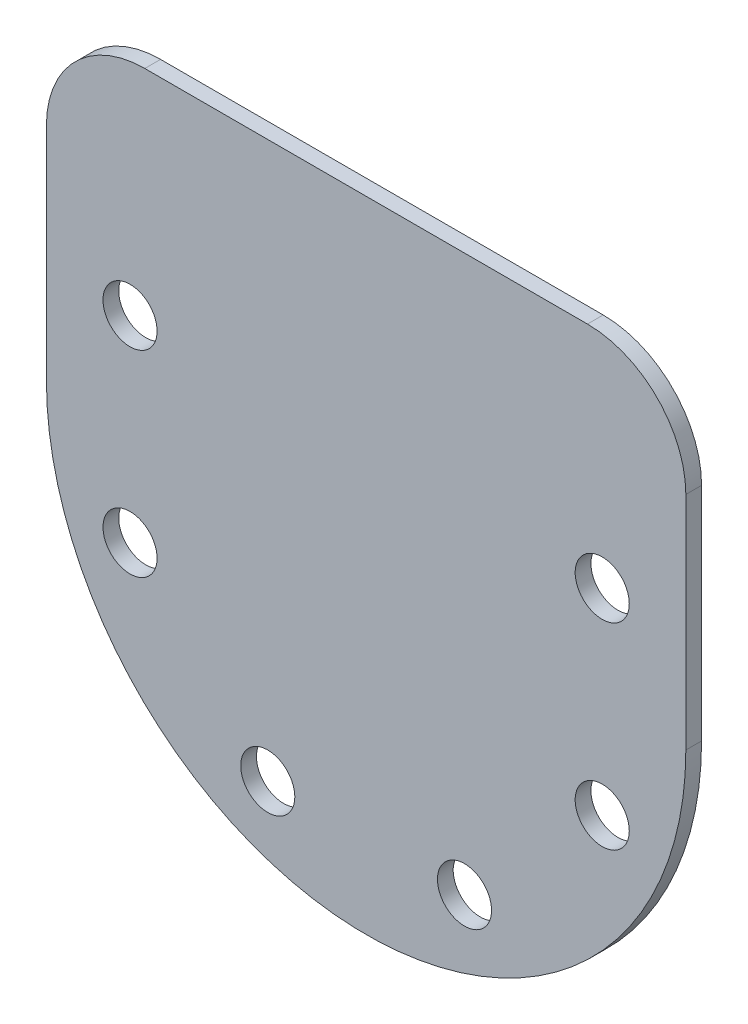
SolidWorks part; units mm, degrees
ref_plane "Front" through (0, 0, 0) normal (0, 0, 1) x (1, 0, 0)
ref_plane "Top" through (0, 0, 0) normal (0, 1, 0) x (1, 0, 0)
ref_plane "Right" through (0, 0, 0) normal (1, 0, 0) x (0, 0, -1)
sketch "Sketch1" plane through (0, 0, 0) normal (0, 0, 1) x (1, 0, 0)
  line L2 (-32.5, 0) -> (-32.5, 32.5)
  line L3 (-32.5, 32.5) -> (32.5, 32.5)
  line L4 (32.5, 0) -> (32.5, 32.5)
  line L5 (-22.981, -22.981) -> (32.5, 32.5) construction
  line L6 (-32.5, 32.5) -> (22.981, -22.981) construction
  arc A0 (-32.5, 0) -> (32.5, 0) centre (0, 0) ccw
  dimension "D1" = 65
  dimension "D2" = 65
extrude "Boss-Extrude1" add sketch "Sketch1" along normal blind 1.6002
hole_wizard "M5 Clearance Hole1" positions "Sketch2" profile "Sketch3" hole size "M5" standard "ANSI Metric" end condition up to next
sketch "Sketch2" plane through (0, 0, 1.6002) normal (0, 0, 1) x (1, 0, 0)
  line L0 (10, -24) -> (-10, -24) construction
  line L11 (-24, -10) -> (-24, 10) construction
  line L13 (24, 10) -> (24, -10) construction
  circle A0 centre (0, 0) radius 26
  point P10 (10, -24)
  point P11 (-10, -24)
  point P58 (-24, -10)
  point P59 (-24, 10)
  point P60 (24, 10)
  point P61 (24, -10)
  dimension "D1" = 52
  dimension "D2" = 20
sketch "Sketch3" plane through (24, -10, 1.6002) normal (1, 0, 0) x (0, -1, 0)
  line L0 (0, 0) -> (0, 1.6002)
  line L1 (0, 1.6002) -> (2.75, 1.6002)
  line L2 (2.75, 1.6002) -> (2.75, 0)
  line L5 (2.75, 0) -> (0, 0)
  line L11 (0, -6.35) -> (0, 107.95) construction
  dimension "Thru Hole Dia." = 5.5
  dimension "Thru Hole Depth" = 1.6002
fillet "Fillet1" radius 10 2 edges at (-32.5, 32.5, 0.8001) (32.5, 32.5, 0.8001)
